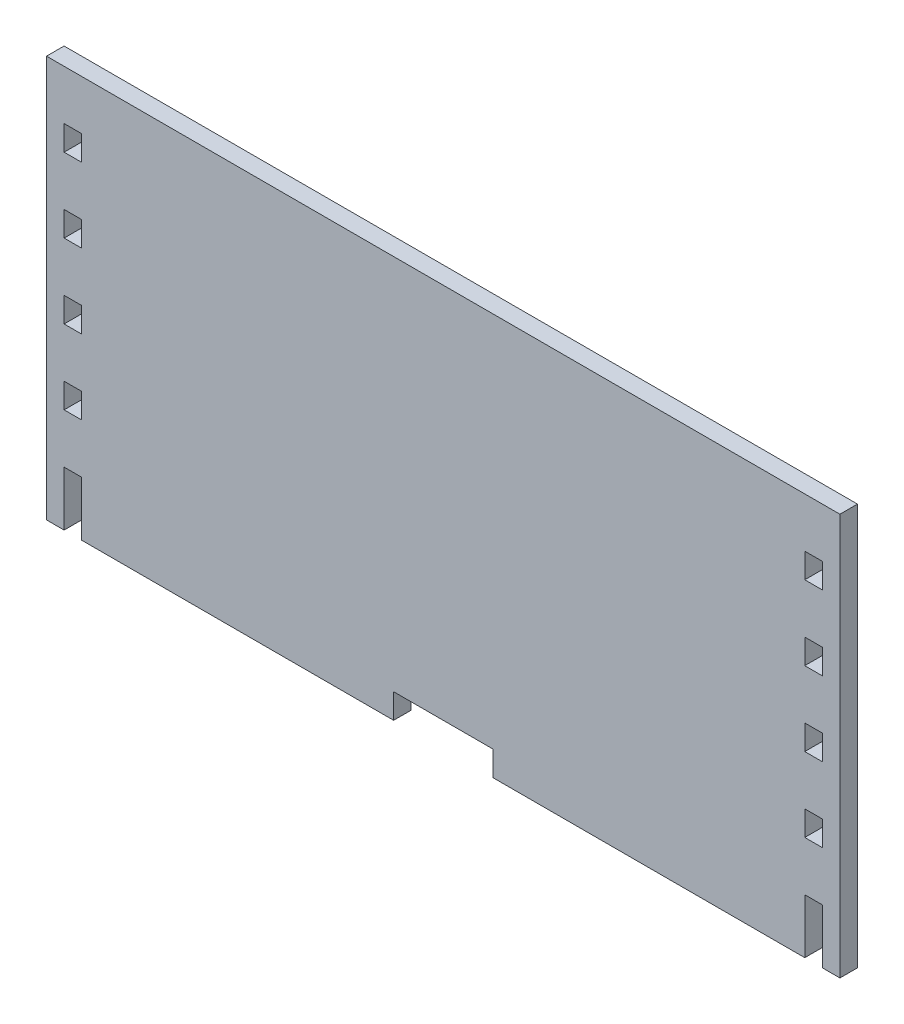
SolidWorks part; units mm, degrees
ref_plane "Front Plane" through (0, 0, 0) normal (0, 0, 1) x (1, 0, 0)
ref_plane "Top Plane" through (0, 0, 0) normal (0, 1, 0) x (1, 0, 0)
ref_plane "Right Plane" through (0, 0, 0) normal (1, 0, 0) x (0, 0, -1)
sketch "Sketch1" plane through (0, 0, 0) normal (0, 0, 1) x (1, 0, 0)
  line L0 (4.5085, 71.12) -> (4.5085, 64.77)
  line L1 (0, 0) -> (203.2, 0)
  line L2 (0, 0) -> (0, 102.87)
  line L3 (0, 102.87) -> (203.2, 102.87)
  line L4 (203.2, 0) -> (203.2, 102.87)
  line L5 (4.5085, 90.17) -> (9.0043, 90.17)
  line L6 (4.5085, 90.17) -> (4.5085, 83.82)
  line L7 (4.5085, 83.82) -> (9.0043, 83.82)
  line L8 (9.0043, 90.17) -> (9.0043, 83.82)
  line L9 (4.5085, 71.12) -> (9.0043, 71.12)
  line L10 (9.0043, 71.12) -> (9.0043, 64.77)
  line L11 (4.5085, 64.77) -> (9.0043, 64.77)
  line L12 (4.5085, 52.07) -> (4.5085, 45.72)
  line L13 (4.5085, 52.07) -> (9.0043, 52.07)
  line L14 (9.0043, 52.07) -> (9.0043, 45.72)
  line L15 (4.5085, 45.72) -> (9.0043, 45.72)
  line L16 (4.5085, 33.02) -> (4.5085, 26.67)
  line L17 (4.5085, 33.02) -> (9.0043, 33.02)
  line L18 (9.0043, 33.02) -> (9.0043, 26.67)
  line L19 (4.5085, 26.67) -> (9.0043, 26.67)
  line L20 (4.5085, 13.97) -> (4.5085, 7.62)
  line L21 (4.5085, 13.97) -> (9.0043, 13.97)
  line L22 (9.0043, 13.97) -> (9.0043, 7.62)
  line L24 (101.6, 102.87) -> (101.6, 0) construction
  line L25 (198.6915, 13.97) -> (194.1957, 13.97)
  line L26 (194.1957, 13.97) -> (194.1957, 7.62)
  line L28 (198.6915, 13.97) -> (198.6915, 7.62)
  line L29 (198.6915, 33.02) -> (194.1957, 33.02)
  line L30 (194.1957, 33.02) -> (194.1957, 26.67)
  line L31 (198.6915, 26.67) -> (194.1957, 26.67)
  line L32 (198.6915, 33.02) -> (198.6915, 26.67)
  line L33 (198.6915, 52.07) -> (194.1957, 52.07)
  line L34 (194.1957, 52.07) -> (194.1957, 45.72)
  line L35 (198.6915, 45.72) -> (194.1957, 45.72)
  line L36 (198.6915, 52.07) -> (198.6915, 45.72)
  line L37 (198.6915, 71.12) -> (194.1957, 71.12)
  line L38 (194.1957, 71.12) -> (194.1957, 64.77)
  line L39 (198.6915, 64.77) -> (194.1957, 64.77)
  line L40 (198.6915, 71.12) -> (198.6915, 64.77)
  line L41 (198.6915, 83.82) -> (194.1957, 83.82)
  line L42 (194.1957, 90.17) -> (194.1957, 83.82)
  line L43 (198.6915, 90.17) -> (194.1957, 90.17)
  line L44 (198.6915, 90.17) -> (198.6915, 83.82)
  line L47 (4.5085, 7.62) -> (4.5085, 0)
  line L48 (4.5085, 0) -> (9.0043, 0)
  line L49 (9.0043, 7.62) -> (9.0043, 0)
  line L51 (194.1957, 7.62) -> (194.1957, 0)
  line L52 (194.1957, 0) -> (198.6915, 0)
  line L53 (198.6915, 7.62) -> (198.6915, 0)
  line L54 (4.5085, 7.62) -> (9.0043, 7.62) [skipped]
  dimension "D1" = 102.87
  dimension "D2" = 203.2
  dimension "D3" = 6.35
  dimension "D4" = 4.4958
  dimension "D5" = 185.1914
  dimension "D7" = 12.7
  dimension "D8" = 12.7
  dimension "D6" = 5
extrude "Boss-Extrude1" add sketch "Sketch1" along normal blind 4.4958 contours L24 L3 L8 L7 L6 L2 L1 L20 L21 L22 L19 L16 L17 L18 L15 L12 L13 L14 L11 L0 L9 L10 | L3 L24 L1 L26 L25 L28 L4 L44 L41 L42 L37 L40 L39 L38 L33 L36 L35 L34 L29 L32 L31 L30
sketch "Sketch2" plane through (0, 0, 4.4958) normal (0, 0, 1) x (1, 0, 0)
  line L0 (9.0043, 0) -> (194.1957, 0) construction
  line L1 (88.9, 0) -> (114.3, 0)
  line L2 (88.9, 0) -> (88.9, 6.35)
  line L3 (88.9, 6.35) -> (114.3, 6.35)
  line L4 (114.3, 0) -> (114.3, 6.35)
  point P6 (101.6, 0)
  point P7 (101.6, 0)
  dimension "D1" = 6.35
  dimension "D2" = 25.4
extrude "Cut-Extrude1" cut sketch "Sketch2" against normal through all
